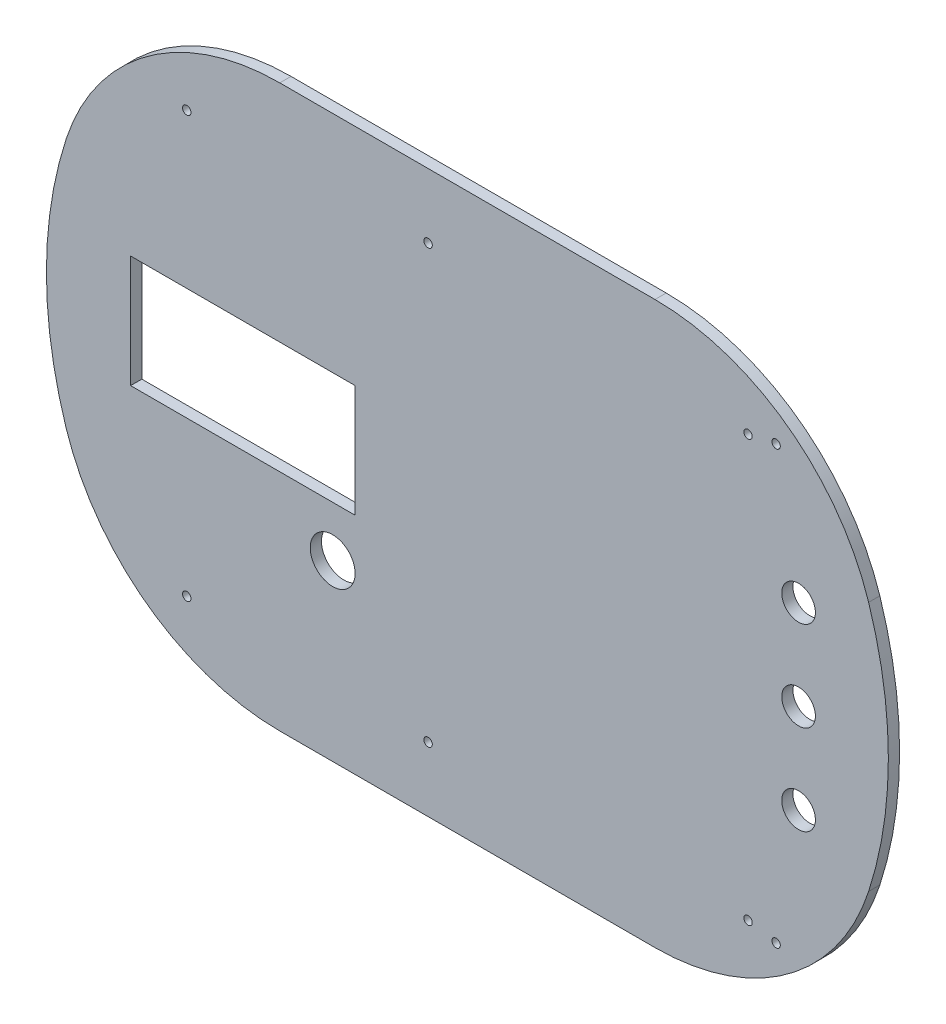
SolidWorks part; units mm, degrees
ref_plane "Front Plane" through (0, 0, 0) normal (0, 0, 1) x (1, 0, 0)
ref_plane "Top Plane" through (0, 0, 0) normal (0, 1, 0) x (1, 0, 0)
ref_plane "Right Plane" through (0, 0, 0) normal (1, 0, 0) x (0, 0, -1)
sketch "Sketch1" plane through (0, 0, 0) normal (0, 0, 1) x (1, 0, 0)
  line L0 (0, 50) -> (0, -50) construction
  line L1 (-55, 50) -> (55, 50)
  line L2 (-55, 50) -> (-55, -50)
  line L3 (-55, -50) -> (55, -50)
  line L4 (55, 50) -> (55, -50)
  line L5 (-55, 50) -> (55, -50) construction
  line L6 (-55, -50) -> (55, 50) construction
  line L7 (-55, 50) -> (-55, -50)
  arc A0 (55, 50) -> (55, -50) centre (2.5, 0) cw
  arc A1 (-55, 50) -> (-55, -50) centre (-2.5, 0) ccw
  point P0 (0, 0)
  point P7 (55, 0)
  point P8 (75, 0)
  dimension "D1" = 110
  dimension "D2" = 20
  dimension "D3" = 100
extrude "Boss-Extrude1" add sketch "Sketch1" along normal blind 2 contours L2 A1 | L4 L1 L2 L3 | A0 L4
fillet "Fillet2" radius 40 4 edges at (55, -50, 1) (-55, -50, 1) (-55, 50, 1) (55, 50, 1)
sketch "Sketch6" plane through (0, 0, 2) normal (0, 0, 1) x (1, 0, 0)
  line L0 (0, 50) -> (0, -50) construction
  line L7 (-33.4233, 50) -> (33.4233, 50) construction
  line L8 (-33.4233, -50) -> (33.4233, -50) construction
  line L9 (-20, -10) -> (-60, -10)
  line L10 (-60, 10) -> (-60, -10)
  line L11 (-20, 10) -> (-60, 10)
  line L12 (-20, 10) -> (-20, -10)
  circle A0 centre (-24, -19) radius 4
  dimension "D4" = 8
  dimension "D1" = 40
  dimension "D2" = 40
  dimension "D3" = 40
  dimension "D5" = 9
  dimension "D6" = 4
extrude "Cut-Extrude4" cut sketch "Sketch6" against normal blind 3
sketch "Sketch7" plane through (0, 0, 2) normal (0, 0, 1) x (1, 0, 0)
  line L0 (24, 42.5) -> (24, -42.5) construction
  line L3 (-11, 38.5) -> (-11, -38.5) construction
  line L4 (-7, 42.5) -> (55, 42.5)
  line L5 (-7, -42.5) -> (55, -42.5) construction
  line L6 (59, 38.5) -> (59, -38.5) construction
  line L7 (-11, 0) -> (59, 0) construction
  arc A0 (-71.4827, 22.3077) -> (-71.4827, -22.3077) centre (-2.5, 0) ccw construction
  arc A1 (-11, -38.5) -> (-7, -42.5) centre (-7, -38.5) ccw
  arc A2 (55, -42.5) -> (59, -38.5) centre (55, -38.5) ccw
  arc A3 (55, 42.5) -> (59, 38.5) centre (55, 38.5) cw
  arc A4 (-7, 42.5) -> (-11, 38.5) centre (-7, 38.5) ccw
  circle A5 centre (-7, 38.5) radius 4
  circle A6 centre (-7, 38.5) radius 0.75
  circle A7 centre (55, 38.5) radius 0.75
  circle A8 centre (55, 38.5) radius 4
  circle A9 centre (55, -38.5) radius 4
  circle A10 centre (55, -38.5) radius 0.75
  circle A11 centre (-7, -38.5) radius 0.75
  circle A12 centre (-7, -38.5) radius 4
  circle A13 centre (59, 16) radius 3
  circle A14 centre (59, 0) radius 3
  circle A15 centre (59, -16) radius 3
  point P3 (-75, 0)
  point P12 (59, -42.5)
  point P15 (59, 42.5)
  point P18 (-11, 42.5)
  dimension "D4" = 4
  dimension "D5" = 8
  dimension "D6" = 1.5
  dimension "D7" = 6
  dimension "D8" = 6
  dimension "D9" = 6
  dimension "D1" = 70
  dimension "D2" = 85
  dimension "D3" = 64
  dimension "D10" = 16
  dimension "16" = 16
extrude "Cut-Extrude7" cut sketch "Sketch7" against normal blind 10 contours A6 | A7 | A10 | A11 | A13 | A15 | A14
sketch "Sketch8" plane through (0, 0, 2) normal (0, 0, 1) x (1, 0, 0)
  line L1 (-50, 37.5) -> (50, 37.5) construction
  line L2 (-50, 37.5) -> (-50, -37.5) construction
  line L3 (-50, -37.5) -> (50, -37.5) construction
  line L4 (50, 37.5) -> (50, -37.5) construction
  line L5 (-50, 37.5) -> (50, -37.5) construction
  line L6 (-50, -37.5) -> (50, 37.5) construction
  circle A0 centre (-50, 37.5) radius 0.75
  circle A1 centre (50, 37.5) radius 0.75
  circle A2 centre (50, -37.5) radius 0.75
  circle A3 centre (-50, -37.5) radius 0.75
  point P0 (0, 0)
  dimension "D3" = 1.5
  dimension "D4" = 1.5
  dimension "D5" = 1.5
  dimension "D6" = 1.5
  dimension "D1" = 100
  dimension "D2" = 75
extrude "Cut-Extrude8" cut sketch "Sketch8" against normal blind 10
